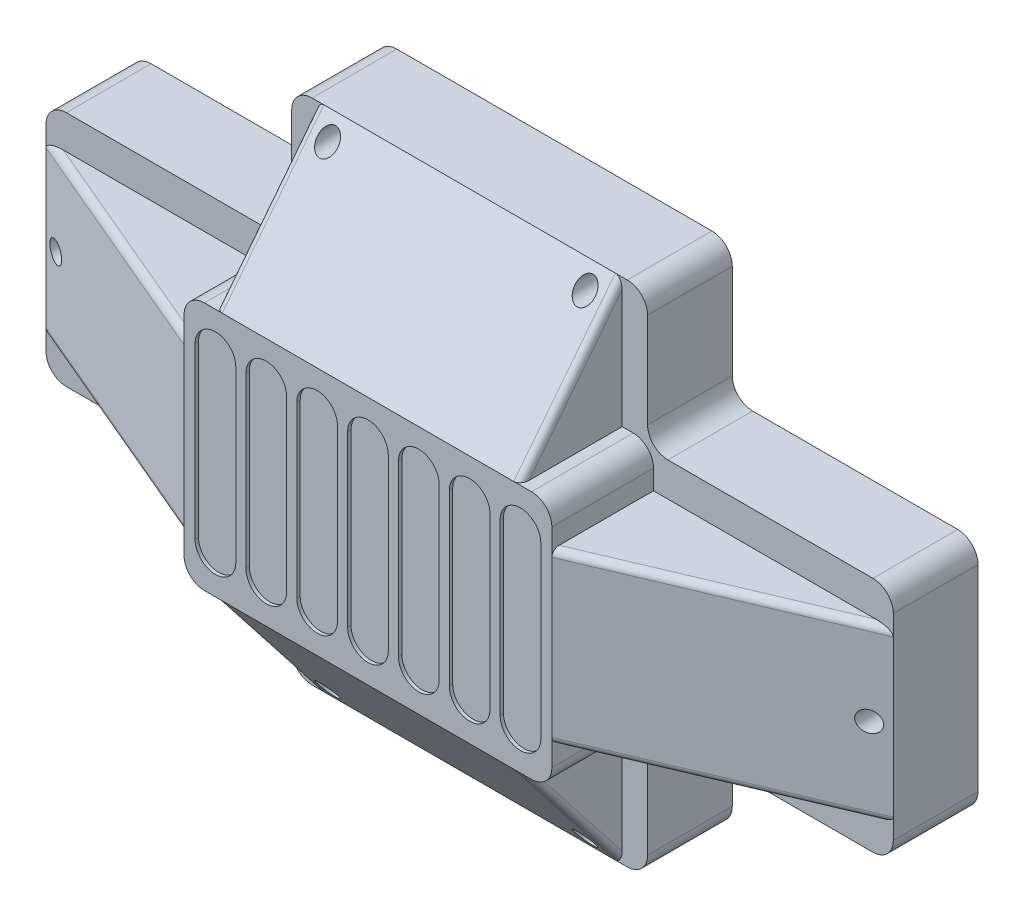
SolidWorks part; units mm, degrees
ref_plane "Front Plane" through (0, 0, 0) normal (0, 0, 1) x (1, 0, 0)
ref_plane "Top Plane" through (0, 0, 0) normal (0, 1, 0) x (1, 0, 0)
ref_plane "Right Plane" through (0, 0, 0) normal (1, 0, 0) x (0, 0, -1)
sketch "Sketch1" plane through (0, 0, 0) normal (0, 0, 1) x (1, 0, 0)
  line L1 (-119, 35) -> (-58.5, 35)
  line L2 (-125, 29) -> (-125, -29)
  line L3 (-119, -35) -> (-58.5, -35)
  line L4 (125, 29) -> (125, -29)
  line L9 (-46.5, 75) -> (46.5, 75)
  line L10 (-52.5, 69) -> (-52.5, 41)
  line L11 (-46.5, -75) -> (46.5, -75)
  line L12 (52.5, 69) -> (52.5, 41)
  line L15 (58.5, 35) -> (119, 35)
  line L17 (-52.5, -41) -> (-52.5, -69)
  line L18 (52.5, -41) -> (52.5, -69)
  line L19 (58.5, -35) -> (119, -35)
  arc A0 (-125, -29) -> (-119, -35) centre (-119, -29) ccw
  arc A1 (-119, 35) -> (-125, 29) centre (-119, 29) ccw
  arc A2 (-52.5, 41) -> (-58.5, 35) centre (-58.5, 41) cw
  arc A3 (52.5, -41) -> (58.5, -35) centre (58.5, -41) cw
  arc A4 (-52.5, -41) -> (-58.5, -35) centre (-58.5, -41) ccw
  arc A5 (-52.5, -69) -> (-46.5, -75) centre (-46.5, -69) ccw
  arc A6 (46.5, -75) -> (52.5, -69) centre (46.5, -69) ccw
  arc A7 (119, -35) -> (125, -29) centre (119, -29) ccw
  arc A8 (119, 35) -> (125, 29) centre (119, 29) cw
  arc A9 (58.5, 35) -> (52.5, 41) centre (58.5, 41) cw
  arc A10 (46.5, 75) -> (52.5, 69) centre (46.5, 69) cw
  arc A11 (-46.5, 75) -> (-52.5, 69) centre (-46.5, 69) ccw
  point P0 (0, 0)
  point P10 (0, 0)
  point P23 (52.5, -35)
  dimension "D1" = 6
extrude "Boss-Extrude1" add sketch "Sketch1" along normal blind 25
sketch "Sketch2" plane through (0, 0, 0) normal (0, 0, -1) x (-1, 0, 0)
  line L1 (41.5, -65) -> (-41.5, -65)
  line L2 (47.5, -59) -> (47.5, -37.5)
  line L3 (41.5, 65) -> (-41.5, 65)
  line L4 (-47.5, -59) -> (-47.5, -37.5)
  line L10 (108.9979, -31.5) -> (53.5, -31.5)
  line L11 (114.9979, -25.5) -> (114.9979, 25.5)
  line L12 (108.9979, 31.5) -> (53.5, 31.5)
  line L13 (-114.9979, -25.5) -> (-114.9979, 25.5)
  line L20 (-53.5, -31.5) -> (-108.9979, -31.5)
  line L22 (47.5, 37.5) -> (47.5, 59)
  line L23 (-53.5, 31.5) -> (-108.9979, 31.5)
  line L24 (-47.5, 37.5) -> (-47.5, 59)
  arc A0 (-108.9979, -31.5) -> (-114.9979, -25.5) centre (-108.9979, -25.5) cw
  arc A1 (-108.9979, 31.5) -> (-114.9979, 25.5) centre (-108.9979, 25.5) ccw
  arc A2 (-41.5, 65) -> (-47.5, 59) centre (-41.5, 59) ccw
  arc A3 (47.5, 59) -> (41.5, 65) centre (41.5, 59) ccw
  arc A4 (114.9979, 25.5) -> (108.9979, 31.5) centre (108.9979, 25.5) ccw
  arc A5 (108.9979, -31.5) -> (114.9979, -25.5) centre (108.9979, -25.5) ccw
  arc A6 (41.5, -65) -> (47.5, -59) centre (41.5, -59) ccw
  arc A7 (-41.5, -65) -> (-47.5, -59) centre (-41.5, -59) cw
  arc A8 (47.5, 37.5) -> (53.5, 31.5) centre (53.5, 37.5) ccw
  arc A9 (-47.5, 37.5) -> (-53.5, 31.5) centre (-53.5, 37.5) cw
  arc A10 (-53.5, -31.5) -> (-47.5, -37.5) centre (-53.5, -37.5) cw
  arc A11 (53.5, -31.5) -> (47.5, -37.5) centre (53.5, -37.5) ccw
  point P0 (0, 0)
  point P8 (0, 0)
  dimension "D1" = 6
extrude "Cut-Extrude1" cut sketch "Sketch2" against normal blind 23
sketch "Sketch3" plane through (0, 0, 25) normal (0, 0, 1) x (1, 0, 0)
  line L1 (-48.2574, 36.7574) -> (48.2574, 36.7574)
  line L2 (-54.2574, 30.7574) -> (-54.2574, -30.7574)
  line L3 (-48.2574, -36.7574) -> (48.2574, -36.7574)
  line L4 (54.2574, 30.7574) -> (54.2574, -30.7574)
  line L5 (-54.2574, 36.7574) -> (54.2574, -36.7574) construction
  line L6 (-54.2574, -36.7574) -> (54.2574, 36.7574) construction
  arc A0 (58.5, -35) -> (52.5, -41) centre (58.5, -41) ccw construction
  arc A1 (-54.2574, -30.7574) -> (-48.2574, -36.7574) centre (-48.2574, -30.7574) ccw
  arc A2 (48.2574, -36.7574) -> (54.2574, -30.7574) centre (48.2574, -30.7574) ccw
  arc A3 (48.2574, 36.7574) -> (54.2574, 30.7574) centre (48.2574, 30.7574) cw
  arc A4 (-48.2574, 36.7574) -> (-54.2574, 30.7574) centre (-48.2574, 30.7574) ccw
  point P0 (0, 0)
  dimension "D1" = 6
extrude "Boss-Extrude2" add sketch "Sketch3" along normal blind 30
sketch "Sketch9" plane through (0, 0, 0) normal (0, 1, 0) x (1, 0, 0)
  line L0 (-125, -25) -> (-54.2574, -55)
rib "Rib5" sketch "Sketch9" sketch "Sketch9" thickness 50 extrusion direction parallel to sketch draft on no parameters "D1"=50
fillet "Fillet2" radius 2 1 edges at (-89.6287, -25, 40)
fillet "Fillet3" radius 2 1 edges at (-89.6287, 25, 40)
mirror "Mirror1" about plane through (0, 0, 0) normal (1, 0, 0) of "Fillet3", "Fillet2", "Rib5"
sketch "Sketch10" plane through (0, 0, 0) normal (1, 0, 0) x (0, 0, -1)
  line L0 (-55, 36.7574) -> (-25, 75)
rib "Rib6" sketch "Sketch10" sketch "Sketch10" thickness 90 extrusion direction parallel to sketch draft on no parameters "D1"=90
fillet "Fillet4" radius 2 2 edges at (-45, 55.8787, 40) (45, 55.8787, 40)
mirror "Mirror3" about plane through (0, 0, 0) normal (0, 1, 0) of "Rib6", "Fillet4"
sketch "Sketch11" plane through (0, 0, 23) normal (0, 0, -1) x (-1, 0, 0)
  line L1 (47.5, -31.5) -> (-47.5, -31.5)
  line L2 (47.5, -31.5) -> (47.5, 31.5)
  line L3 (47.5, 31.5) -> (-47.5, 31.5)
  line L4 (-47.5, -31.5) -> (-47.5, 31.5)
  line L5 (47.5, -31.5) -> (-47.5, 31.5) construction
  line L6 (47.5, 31.5) -> (-47.5, -31.5) construction
  point P0 (0, 0)
extrude "Cut-Extrude2" cut sketch "Sketch11" against normal blind 30
sketch "Sketch12" plane through (0, 0, 55) normal (0, 0, 1) x (1, 0, 0)
  line L0 (0, 25) -> (0, -25) construction
  line L1 (6, 25) -> (6, -25)
  line L2 (-6, 25) -> (-6, -25)
  line L3 (0, -44) -> (0, 44) construction
  line L4 (15, 25) -> (15, -25) construction
  line L5 (21, 25) -> (21, -25)
  line L6 (9, 25) -> (9, -25)
  line L7 (30, 25) -> (30, -25) construction
  line L8 (36, 25) -> (36, -25)
  line L9 (24, 25) -> (24, -25)
  line L10 (45, 25) -> (45, -25) construction
  line L11 (51, 25) -> (51, -25)
  line L12 (39, 25) -> (39, -25)
  line L13 (-45, 25) -> (-45, -25) construction
  line L14 (-51, 25) -> (-51, -25)
  line L15 (-39, 25) -> (-39, -25)
  line L16 (-30, 25) -> (-30, -25) construction
  line L17 (-36, 25) -> (-36, -25)
  line L18 (-24, 25) -> (-24, -25)
  line L19 (-15, 25) -> (-15, -25) construction
  line L20 (-21, 25) -> (-21, -25)
  line L21 (-9, 25) -> (-9, -25)
  arc A0 (6, 25) -> (-6, 25) centre (0, 25) ccw
  arc A1 (-6, -25) -> (6, -25) centre (0, -25) ccw
  arc A2 (21, 25) -> (9, 25) centre (15, 25) ccw
  arc A3 (9, -25) -> (21, -25) centre (15, -25) ccw
  arc A4 (36, 25) -> (24, 25) centre (30, 25) ccw
  arc A5 (24, -25) -> (36, -25) centre (30, -25) ccw
  arc A6 (51, 25) -> (39, 25) centre (45, 25) ccw
  arc A7 (39, -25) -> (51, -25) centre (45, -25) ccw
  arc A8 (-51, 25) -> (-39, 25) centre (-45, 25) cw
  arc A9 (-39, -25) -> (-51, -25) centre (-45, -25) cw
  arc A10 (-36, 25) -> (-24, 25) centre (-30, 25) cw
  arc A11 (-24, -25) -> (-36, -25) centre (-30, -25) cw
  arc A12 (-21, 25) -> (-9, 25) centre (-15, 25) cw
  arc A13 (-9, -25) -> (-21, -25) centre (-15, -25) cw
  point P2 (0, 0)
  point P14 (15, 0)
  point P21 (30, 0)
  point P28 (45, 0)
  point P33 (-45, 0)
  point P40 (-30, 0)
  point P47 (-15, 0)
  dimension "D2" = 6
  dimension "D1" = 50
  dimension "D3" = 4
extrude "Cut-Extrude3" cut sketch "Sketch12" against normal blind 1
sketch "Sketch14" plane through (-125, 0, 0) normal (-1, 0, 0) x (0, 0, 1)
  circle A0 centre (12.5, 14) radius 9
  circle A1 centre (12.5, -14) radius 9
extrude "Cut-Extrude4" cut sketch "Sketch14" against normal blind 5
fillet "Fillet6" radius 3 1 edges at (-120, 14, 21.5)
fillet "Fillet7" radius 3 1 edges at (-120, -14, 21.5)
sketch "Sketch21" plane through (0, 0, 55) normal (0, 0, 1) x (1, 0, 0)
  line L2 (0, -44) -> (0, 44) construction
  line L3 (30.25, 0) -> (-30.25, 0) construction
  circle A0 centre (-38, 70) radius 3
  circle A1 centre (38, 70) radius 3
  circle A2 centre (38, -70) radius 3
  circle A3 centre (-38, -70) radius 3
  circle A4 centre (-120, 0) radius 3
  circle A5 centre (120, 0) radius 3
extrude "Cut-Extrude5" cut sketch "Sketch21" against normal up to surface (55 mm away)
